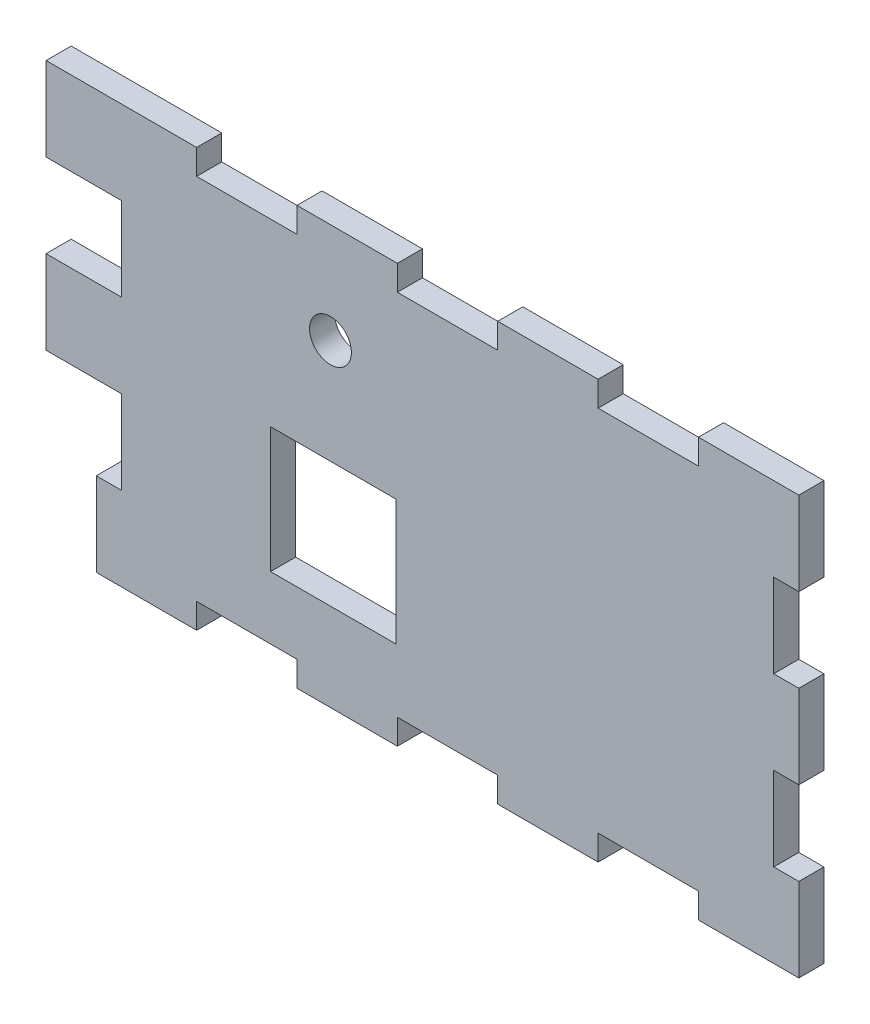
SolidWorks part; units mm, degrees
material "Balsa"
ref_plane "Front" through (0, 0, 0) normal (0, 0, 1) x (1, 0, 0)
ref_plane "Top" through (0, 0, 0) normal (0, 1, 0) x (1, 0, 0)
ref_plane "Right" through (0, 0, 0) normal (1, 0, 0) x (0, 0, -1)
sketch "Esboço4" plane through (0, 0, 0) normal (0, 0, 1) x (1, 0, 0)
  line L1 (42, -25) -> (-42, -25)
  line L2 (42, -25) -> (42, 25)
  line L3 (42, 25) -> (-42, 25)
  line L4 (-42, -25) -> (-42, 25)
  line L5 (42, -25) -> (-42, 25) construction
  line L6 (42, 25) -> (-42, -25) construction
  point P0 (0, 0)
  dimension "D1" = 84
  dimension "D2" = 50
extrude "Ressalto-extrusão2" add sketch "Esboço4" along normal blind 3
sketch "Esboço5" plane through (0, 0, 3) normal (0, 0, 1) x (1, 0, 0)
  line L0 (18, 25) -> (30, 25)
  line L1 (-18, 22) -> (-30, 22)
  line L2 (-6, 25) -> (6, 25)
  line L3 (6, 22) -> (-6, 22)
  line L4 (-30, 25) -> (-30, 22)
  line L5 (-18, 25) -> (-18, 22)
  line L6 (-6, -22) -> (6, -22)
  line L7 (-6, 25) -> (-6, 22)
  line L8 (-18, -25) -> (-30, -25)
  line L9 (6, 25) -> (6, 22)
  line L10 (6, -25) -> (-6, -25)
  line L11 (18, 25) -> (18, 22)
  line L12 (18, -22) -> (30, -22)
  line L13 (30, 25) -> (30, 22)
  line L17 (-18, -22) -> (-18, -25)
  line L19 (-6, -22) -> (-6, -25)
  line L21 (6, -22) -> (6, -25)
  line L23 (18, -22) -> (18, -25)
  line L25 (30, -22) -> (30, -25)
  line L31 (-30, -22) -> (-30, -25)
  line L32 (-30, 25) -> (-18, 25)
  line L33 (30, 22) -> (18, 22)
  line L34 (-30, -22) -> (-18, -22)
  line L35 (30, -25) -> (18, -25)
  line L37 (42, 25) -> (42, 22) [skipped]
  line L38 (42, -22) -> (42, -25) [skipped]
  dimension "D2" = 3
  dimension "D3" = 4
  dimension "D4" = 2
extrude "Corte-extrusão2" cut sketch "Esboço5" against normal up to next
sketch "Esboço6" plane through (0, 0, 0) normal (0, 0, 1) x (1, 0, 0)
  line L0 (42, 5) -> (42, 15)
  line L1 (-42, 15) -> (-42, 5)
  line L2 (-39, 5) -> (-39, 15)
  line L3 (39, 15) -> (39, 5)
  line L4 (-42, -5) -> (-42, -15)
  line L5 (42, -15) -> (42, -5)
  line L6 (-39, -15) -> (-39, -5)
  line L7 (39, -5) -> (39, -15)
  line L9 (-42, 15) -> (-39, 15)
  line L12 (39, 15) -> (42, 15)
  line L14 (39, 5) -> (42, 5)
  line L16 (39, -5) -> (42, -5)
  line L18 (39, -15) -> (42, -15)
  line L22 (-42, 5) -> (-39, 5)
  line L24 (-42, -5) -> (-39, -5)
  line L26 (-42, -15) -> (-39, -15)
  line L39 (-42, -25) -> (-39, -25) [skipped]
  line L40 (39, -25) -> (42, -25) [skipped]
  point P0 (0, 0)
  dimension "D5" = 2
  dimension "D6" = 3
extrude "Corte-extrusão4" cut sketch "Esboço6" along normal up to next
sketch "Esboço7" plane through (0, 0, 0) normal (0, 0, 1) x (1, 0, 0)
  line L1 (42, -25) -> (-42, -25)
  line L2 (42, -25) -> (42, 25)
  line L3 (42, 25) -> (-42, 25)
  line L4 (-42, -25) -> (-42, 25)
  line L5 (42, -25) -> (-42, 25) construction
  line L6 (42, 25) -> (-42, -25) construction
  point P0 (0, 0)
  dimension "D1" = 84
  dimension "D2" = 50
sketch "Esboço8" plane through (0, 0, 0) normal (0, 0, -1) x (-1, 0, 0)
  line L0 (-42, -25) -> (42, -25) construction
  line L6 (21.1576, -14.5) -> (6.1576, -14.5)
  line L7 (21.1576, -14.5) -> (21.1576, 0.5)
  line L8 (21.1576, 0.5) -> (6.1576, 0.5)
  line L9 (6.1576, -14.5) -> (6.1576, 0.5)
  line L10 (21.1576, -14.5) -> (6.1576, 0.5) construction
  line L11 (21.1576, 0.5) -> (6.1576, -14.5) construction
  circle A0 centre (13.9973, 13) radius 2.5
  point P0 (13.6576, -7)
  point P5 (-0.0027, -25)
  dimension "D1" = 18
  dimension "D4" = 15
  dimension "D5" = 15
extrude "Corte-extrusão5" cut sketch "Esboço8" against normal up to next
sketch "Esboço11" plane through (-42, 0, 0) normal (-1, 0, 0) x (0, 0, 1)
  line L4 (0, -5) -> (3, -5) construction
  line L5 (3, -5) -> (3, 5) construction
  line L6 (3, 5) -> (0, 5) construction
  line L7 (0, 5) -> (0, -5) construction
  line L8 (0, 15) -> (3, 15) construction
  line L9 (3, 15) -> (3, 25) construction
  line L10 (3, 25) -> (0, 25) construction
  line L11 (0, 25) -> (0, 15) construction
  line L16 (0, -5) -> (3, -5)
  line L17 (3, -5) -> (3, 5)
  line L18 (3, 5) -> (0, 5)
  line L19 (0, 5) -> (0, -5)
  line L20 (0, 15) -> (3, 15)
  line L21 (3, 15) -> (3, 25)
  line L22 (3, 25) -> (0, 25)
  line L23 (0, 25) -> (0, 15)
extrude "Ressalto-extrusão4" add sketch "Esboço11" along normal blind 6
